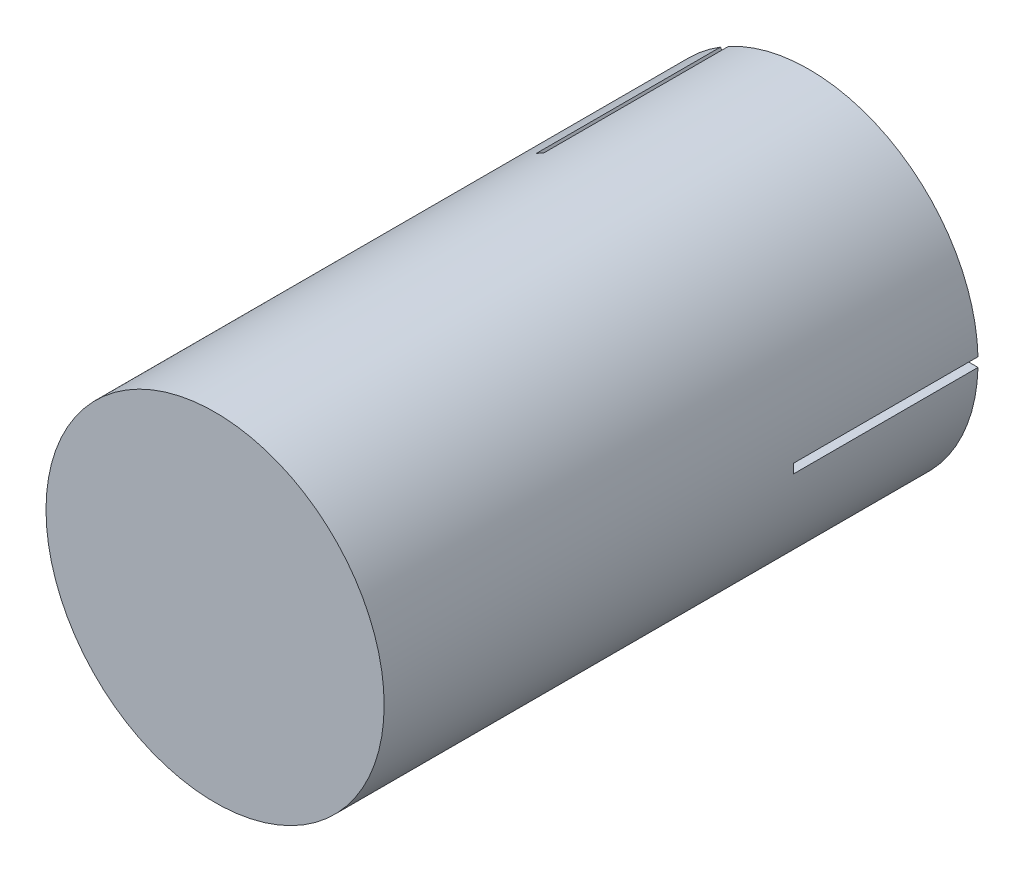
SolidWorks part; units mm, degrees
ref_plane "前视基准面" through (0, 0, 0) normal (0, 0, 1) x (1, 0, 0)
ref_plane "上视基准面" through (0, 0, 0) normal (0, 1, 0) x (1, 0, 0)
ref_plane "右视基准面" through (0, 0, 0) normal (1, 0, 0) x (0, 0, -1)
other "Configuration Table"
sketch "草图1" plane through (0, 0, 0) normal (0, 0, 1) x (1, 0, 0)
  circle A1 centre (0, 0) radius 55
  dimension "D1" = 110
extrude "凸台-拉伸1" add sketch "草图1" along normal blind 190
sketch "草图2" plane through (0, 0, 190) normal (0, 0, 1) x (1, 0, 0)
  circle A0 centre (0, 0) radius 51.8
  dimension "D1" = 103.6
extrude "切除-拉伸1" cut sketch "草图2" against normal blind 186.8
sketch "草图3" plane through (0, 0, 0) normal (0, 0, -1) x (-1, 0, 0)
  circle A0 centre (0, 0) radius 15
  dimension "D1" = 30
extrude "切除-拉伸2" cut sketch "草图3" against normal blind 10
sketch "草图4" plane through (0, 0, 3.2) normal (0, 0, 1) x (1, 0, 0)
  circle A0 centre (0, 0) radius 15
  circle A1 centre (0, 0) radius 18.2
  dimension "D1" = 36.4
extrude "凸台-拉伸2" add sketch "草图4" along normal blind 188
sketch "草图5" plane through (0, 0, 190) normal (0, 0, 1) x (1, 0, 0)
  circle A0 centre (0, 0) radius 55
extrude "凸台-拉伸5" add sketch "草图5" along normal blind 3.2
sketch "草图6" plane through (0, 0, 193.2) normal (0, 0, 1) x (1, 0, 0)
  line L0 (0, 0) -> (-55, 0)
  line L1 (0, 0) -> (27.5, 47.6314)
  line L2 (0, 0) -> (27.5, -47.6314)
  circle A0 centre (0, 0) radius 55 construction
  point P10 (0, 0)
  dimension "D1" = 3
ref_plane "基准面1" through (0, 0, 0) normal (0, 1, 0) x (-1, 0, 0)
sketch "草图8" plane through (0, 0, 0) normal (0, 1, 0) x (-1, 0, 0)
  line L0 (-55, 90) -> (-135, 65)
  line L1 (-55, 193.2) -> (-55, 0) construction
  line L2 (-135, 65) -> (-135, -15)
  line L3 (-135, -15) -> (-55, 0)
  line L5 (-55, 90) -> (-53, 90)
  line L6 (-53, 90) -> (-53, 0)
  line L7 (-55, 0) -> (55, 0) construction
  line L8 (-53, 0) -> (-55, 0)
  dimension "D1" = 65
  dimension "D2" = 25
  dimension "D3" = 80
  dimension "D4" = 2
  dimension "D5" = 80
extrude "凸台-拉伸6" add sketch "草图8" along normal mid plane 3
sketch "草图9" plane through (0, 0, 0) normal (0, 0, -1) x (-1, 0, 0)
  line L0 (0, 0) -> (-135, 0) construction
  line L1 (-135, 1.5) -> (-135, -1.5) construction
  line L2 (-51.1785, 8) -> (-47.8664, 9.5)
  line L3 (-51.1785, -8) -> (-47.8664, -9.5)
  line L8 (-47.8664, 9.5) -> (-44.5994, 9.5)
  line L9 (-47.8664, -9.5) -> (-44.5994, -9.5)
  line L10 (32.5175, 40.3219) -> (32.1604, 36.7035)
  line L11 (32.1604, 36.7035) -> (30.527, 33.8742)
  line L12 (15.7059, 46.2035) -> (14.0725, 43.3742)
  line L13 (18.6611, 48.3219) -> (15.7059, 46.2035)
  line L14 (18.6611, -48.3219) -> (15.7059, -46.2035)
  line L15 (15.7059, -46.2035) -> (14.0725, -43.3742)
  line L16 (32.1604, -36.7035) -> (30.527, -33.8742)
  line L17 (32.5175, -40.3219) -> (32.1604, -36.7035)
  arc A0 (-51.1785, 8) -> (-51.1785, -8) centre (0, 0) ccw
  arc A7 (-44.5994, 9.5) -> (-44.5994, -9.5) centre (0, 0) ccw
  arc A8 (32.5175, 40.3219) -> (18.6611, 48.3219) centre (0, 0) ccw
  arc A9 (30.527, 33.8742) -> (14.0725, 43.3742) centre (0, 0) ccw
  arc A10 (18.6611, -48.3219) -> (32.5175, -40.3219) centre (0, 0) ccw
  arc A11 (14.0725, -43.3742) -> (30.527, -33.8742) centre (0, 0) ccw
  point P19 (0, 0)
  point P26 (0, 0)
  dimension "D1" = 103.6
  dimension "D2" = 3
  dimension "D6" = 91.2
  dimension "D4" = 8
  dimension "D5" = 9.5
extrude "凸台-拉伸7" add sketch "草图9" against normal blind 63.2
sketch "草图11" plane through (0, 0, 0) normal (0, 0, -1) x (-1, 0, 0)
  line L0 (-55, 0) -> (0, 0) construction
  line L1 (-55, 1.5) -> (-55, -1.5) construction
  line L2 (-65.9984, 1.5) -> (-51.7783, 1.5)
  line L3 (-135, 1.5) -> (-55, 1.5) construction
  line L6 (-65.9984, -1.5) -> (-51.7783, -1.5)
  line L7 (-65.9984, 1.5) -> (-65.9984, -1.5)
  line L8 (-51.5581, 5) -> (-48.2953, 7)
  line L9 (-51.5581, -5) -> (-48.2953, -7)
  line L10 (34.2982, 56.4063) -> (31.7001, 57.9063)
  line L11 (34.2982, 56.4063) -> (27.1882, 44.0913)
  line L12 (31.7001, 57.9063) -> (24.5901, 45.5913)
  line L13 (30.1092, 42.1506) -> (30.2098, 38.325)
  line L14 (21.4489, 47.1506) -> (18.0855, 45.325)
  line L15 (31.7001, -57.9063) -> (34.2982, -56.4063)
  line L16 (31.7001, -57.9063) -> (24.5901, -45.5913)
  line L17 (34.2982, -56.4063) -> (27.1882, -44.0913)
  line L18 (21.4489, -47.1506) -> (18.0855, -45.325)
  line L19 (30.1092, -42.1506) -> (30.2098, -38.325)
  arc A1 (-48.2953, 7) -> (-48.2953, -7) centre (0, 0) ccw
  arc A3 (-51.5581, 5) -> (-51.7783, 1.5) centre (0, 0) ccw
  arc A4 (-51.5581, -5) -> (-51.7783, -1.5) centre (0, 0) cw
  arc A5 (30.1092, 42.1506) -> (27.1882, 44.0913) centre (0, 0) ccw
  arc A6 (30.2098, 38.325) -> (18.0855, 45.325) centre (0, 0) ccw
  arc A7 (21.4489, 47.1506) -> (24.5901, 45.5913) centre (0, 0) cw
  arc A8 (21.4489, -47.1506) -> (24.5901, -45.5913) centre (0, 0) ccw
  arc A9 (18.0855, -45.325) -> (30.2098, -38.325) centre (0, 0) ccw
  arc A10 (30.1092, -42.1506) -> (27.1882, -44.0913) centre (0, 0) cw
  point P34 (0, 0)
  dimension "D1" = 7
  dimension "D2" = 3
  dimension "D3" = 97.6
  dimension "D4" = 5
  dimension "D5" = 103.6
  dimension "D6" = 3
extrude "切除-拉伸4" cut sketch "草图11" against normal blind 60
sketch "草图12" plane through (0, 0, 0) normal (0, 0, -1) x (-1, 0, 0)
  circle A0 centre (0, 0) radius 138.3674
  circle A1 centre (0, 0) radius 55
extrude "切除-拉伸5" cut sketch "草图12" against normal mid plane 270
sketch "草图13" plane through (0, 0, 0) normal (0, 0, -1) x (-1, 0, 0)
  line L0 (4, 27.1109) -> (4, 36.3318)
  line L1 (-4, 27.1109) -> (-4, 36.3318)
  line L2 (27.1109, 4) -> (36.3318, 4)
  line L3 (-27.1109, 4) -> (-36.3318, 4)
  line L4 (27.1109, -4) -> (36.3318, -4)
  line L5 (4, -27.1109) -> (4, -36.3318)
  line L6 (-4, -27.1109) -> (-4, -36.3318)
  line L7 (-27.1109, -4) -> (-36.3318, -4)
  arc A0 (-7.5676, 39.2776) -> (-39.2776, 7.5676) centre (0, 0) ccw
  arc A1 (-6.25, 24.2061) -> (-24.2061, 6.25) centre (0, 0) ccw
  arc A2 (-4, 36.3318) -> (-7.5676, 39.2776) centre (-7, 36.3318) ccw
  arc A3 (-6.25, 24.2061) -> (-4, 27.1109) centre (-7, 27.1109) ccw
  arc A4 (-24.2061, 6.25) -> (-27.1109, 4) centre (-27.1109, 7) cw
  arc A5 (-36.3318, 4) -> (-39.2776, 7.5676) centre (-36.3318, 7) cw
  arc A6 (39.2776, 7.5676) -> (7.5676, 39.2776) centre (0, 0) ccw
  arc A7 (24.2061, 6.25) -> (6.25, 24.2061) centre (0, 0) ccw
  arc A8 (4, 36.3318) -> (7.5676, 39.2776) centre (7, 36.3318) cw
  arc A9 (6.25, 24.2061) -> (4, 27.1109) centre (7, 27.1109) cw
  arc A10 (36.3318, 4) -> (39.2776, 7.5676) centre (36.3318, 7) ccw
  arc A11 (24.2061, 6.25) -> (27.1109, 4) centre (27.1109, 7) ccw
  arc A12 (7.5676, -39.2776) -> (39.2776, -7.5676) centre (0, 0) ccw
  arc A13 (6.25, -24.2061) -> (24.2061, -6.25) centre (0, 0) ccw
  arc A14 (36.3318, -4) -> (39.2776, -7.5676) centre (36.3318, -7) cw
  arc A15 (24.2061, -6.25) -> (27.1109, -4) centre (27.1109, -7) cw
  arc A16 (4, -36.3318) -> (7.5676, -39.2776) centre (7, -36.3318) ccw
  arc A17 (6.25, -24.2061) -> (4, -27.1109) centre (7, -27.1109) ccw
  arc A18 (-39.2776, -7.5676) -> (-7.5676, -39.2776) centre (0, 0) ccw
  arc A19 (-24.2061, -6.25) -> (-6.25, -24.2061) centre (0, 0) ccw
  arc A20 (-4, -36.3318) -> (-7.5676, -39.2776) centre (-7, -36.3318) cw
  arc A21 (-6.25, -24.2061) -> (-4, -27.1109) centre (-7, -27.1109) cw
  arc A22 (-36.3318, -4) -> (-39.2776, -7.5676) centre (-36.3318, -7) ccw
  arc A23 (-24.2061, -6.25) -> (-27.1109, -4) centre (-27.1109, -7) ccw
  point P7 (-4, 39.7995)
  point P11 (-4, 24.6779)
  point P14 (-24.6779, 4)
  point P17 (-39.7995, 4)
  point P57 (0, 0)
  dimension "D1" = 80
  dimension "D2" = 50
  dimension "D5" = 3
  dimension "D6" = 3
  dimension "D7" = 3
  dimension "D8" = 3
  dimension "D3" = 15.1216
  dimension "D4" = 15.1216
  dimension "D9" = 4
extrude "切除-拉伸6" cut sketch "草图13" against normal blind 10
equation "\"3。2\"=1"
